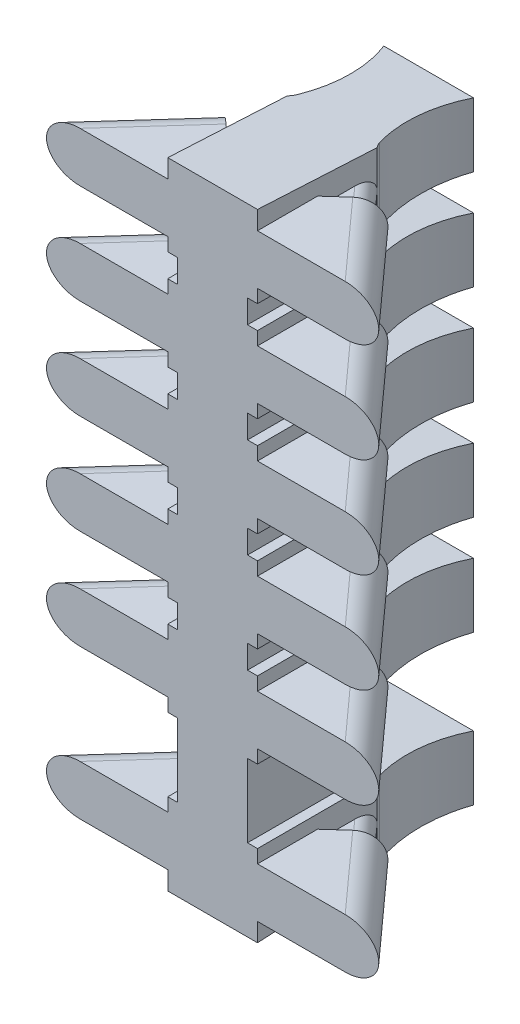
SolidWorks part; units mm, degrees
ref_plane "Front Plane" through (0, 0, 0) normal (0, 0, 1) x (1, 0, 0)
ref_plane "Top Plane" through (0, 0, 0) normal (0, 1, 0) x (1, 0, 0)
ref_plane "Right Plane" through (0, 0, 0) normal (1, 0, 0) x (0, 0, -1)
sketch "Sketch1" plane through (0, 0, 0) normal (0, 0, 1) x (1, 0, 0)
  line L0 (-7.5, 0) -> (0, 0) construction
  line L1 (-7.5, 15) -> (7.5, 15)
  line L2 (-7.5, 15) -> (-7.5, -15)
  line L3 (-7.5, -15) -> (7.5, -15)
  line L4 (7.5, 15) -> (7.5, -15)
  line L5 (0, 0) -> (0, 15) construction
  dimension "D1" = 15
  dimension "D2" = 30
sketch "Sketch2" plane through (0, 0, 0) normal (1, 0, 0) x (0, 0, -1)
  line L1 (0, 15) -> (7, 15)
  line L2 (0, 15) -> (0, -15)
  line L3 (0, -15) -> (7, -15)
  line L4 (7, 15) -> (7, -15)
  dimension "D1" = 7
extrude "Boss-Extrude1" add sketch "Sketch1" against normal up to vertex (7 mm away) up to point (0, 15, -7)
ref_plane "Plane1" through (1.35, 0, 0) normal (1, 0, 0) x (0, 0, -1)
sketch "Sketch7" plane through (1.35, 0, 0) normal (1, 0, 0) x (0, 0, -1)
  line L0 (3, 4.1005) -> (0, 4.1005) construction
  line L1 (0, 4.1005) -> (0, 6.3995) construction
  line L2 (3, 6.3995) -> (0, 6.3995) construction
  line L3 (3, 6.3995) -> (6.5, 6.2161) construction
  line L4 (6.5, 6.2161) -> (6.5, 4.2839) construction
  line L5 (6.5, 4.2839) -> (3, 4.1005) construction
  line L6 (3, 1.1005) -> (0, 1.1005) construction
  line L7 (0, 1.1005) -> (0, 3.3995) construction
  line L8 (3, 3.3995) -> (0, 3.3995) construction
  line L9 (6.5, 3.2161) -> (3, 3.3995) construction
  line L10 (6.5, 1.2839) -> (6.5, 3.2161) construction
  line L11 (3, 1.1005) -> (6.5, 1.2839) construction
  line L12 (3, -1.8995) -> (0, -1.8995) construction
  line L13 (0, -1.8995) -> (0, 0.3995) construction
  line L14 (3, 0.3995) -> (0, 0.3995) construction
  line L15 (3, 0.3995) -> (6.5, 0.2161) construction
  line L16 (6.5, 0.2161) -> (6.5, -1.7161) construction
  line L17 (6.5, -1.7161) -> (3, -1.8995) construction
  line L19 (3, -4.8995) -> (0, -4.8995) construction
  line L20 (0, -4.8995) -> (0, -2.6005) construction
  line L21 (3, -2.6005) -> (0, -2.6005) construction
  line L22 (6.5, -2.7839) -> (3, -2.6005) construction
  line L23 (6.5, -4.7161) -> (6.5, -2.7839) construction
  line L24 (3, -4.8995) -> (6.5, -4.7161) construction
  line L25 (3, -7.1005) -> (0, -7.1005) construction
  line L26 (0, -9.5567) -> (0, -7.1005) construction
  line L27 (6.5, -9.2161) -> (0, -9.5567) construction
  line L28 (6.5, -7.2839) -> (6.5, -9.2161) construction
  line L29 (3, -7.1005) -> (6.5, -7.2839) construction
  line L30 (3, 7.1005) -> (0, 7.1005) construction
  line L31 (0, 7.1005) -> (0, 9.5567) construction
  line L32 (6.5, 9.2161) -> (0, 9.5567) construction
  line L33 (6.5, 7.2839) -> (6.5, 9.2161) construction
  line L34 (3, 7.1005) -> (6.5, 7.2839) construction
  line L35 (3, 4.1005) -> (0, 4.1005)
  line L36 (0, 4.1005) -> (0, 6.3995)
  line L37 (3, 6.3995) -> (0, 6.3995)
  line L38 (3, 6.3995) -> (6.5, 6.2161)
  line L39 (6.5, 6.2161) -> (6.5, 4.2839)
  line L40 (6.5, 4.2839) -> (3, 4.1005)
  line L41 (3, 1.1005) -> (0, 1.1005)
  line L42 (0, 1.1005) -> (0, 3.3995)
  line L43 (3, 3.3995) -> (0, 3.3995)
  line L44 (6.5, 3.2161) -> (3, 3.3995)
  line L45 (6.5, 1.2839) -> (6.5, 3.2161)
  line L46 (3, 1.1005) -> (6.5, 1.2839)
  line L47 (3, -1.8995) -> (0, -1.8995)
  line L48 (0, -1.8995) -> (0, 0.3995)
  line L49 (3, 0.3995) -> (0, 0.3995)
  line L50 (3, 0.3995) -> (6.5, 0.2161)
  line L51 (6.5, 0.2161) -> (6.5, -1.7161)
  line L52 (6.5, -1.7161) -> (3, -1.8995)
  line L54 (3, -4.8995) -> (0, -4.8995)
  line L55 (0, -4.8995) -> (0, -2.6005)
  line L56 (3, -2.6005) -> (0, -2.6005)
  line L57 (6.5, -2.7839) -> (3, -2.6005)
  line L58 (6.5, -4.7161) -> (6.5, -2.7839)
  line L59 (3, -4.8995) -> (6.5, -4.7161)
  line L60 (3, -7.1005) -> (0, -7.1005)
  line L61 (0, -9.5567) -> (0, -7.1005)
  line L62 (6.5, -9.2161) -> (0, -9.5567)
  line L63 (6.5, -7.2839) -> (6.5, -9.2161)
  line L64 (3, -7.1005) -> (6.5, -7.2839)
  line L65 (3, 7.1005) -> (0, 7.1005)
  line L66 (0, 7.1005) -> (0, 9.5567)
  line L67 (6.5, 9.2161) -> (0, 9.5567)
  line L68 (6.5, 7.2839) -> (6.5, 9.2161)
  line L69 (3, 7.1005) -> (6.5, 7.2839)
sketch "Sketch8" plane through (1.35, 0, 0) normal (1, 0, 0) x (0, 0, -1)
  line L0 (6.5, -4.7161) -> (6.5, -2.7839) construction
  line L1 (6.5, -2.7839) -> (3, -2.6005) construction
  line L2 (3, -2.6005) -> (3, -1.8995) construction
  line L3 (6.5, -1.7161) -> (3, -1.8995) construction
  line L4 (6.5, 0.2161) -> (6.5, -1.7161) construction
  line L5 (3, 0.3995) -> (6.5, 0.2161) construction
  line L6 (3, 0.3995) -> (3, 1.1005) construction
  line L7 (3, 1.1005) -> (6.5, 1.2839) construction
  line L8 (6.5, 1.2839) -> (6.5, 3.2161) construction
  line L9 (6.5, 3.2161) -> (3, 3.3995) construction
  line L10 (3, 3.3995) -> (3, 4.1005) construction
  line L11 (6.5, 4.2839) -> (3, 4.1005) construction
  line L12 (6.5, 6.2161) -> (6.5, 4.2839) construction
  line L13 (3, 6.3995) -> (6.5, 6.2161) construction
  line L14 (3, 6.3995) -> (3, 7.1005) construction
  line L15 (3, 7.1005) -> (6.5, 7.2839) construction
  line L16 (6.5, 7.2839) -> (6.5, 9.2161) construction
  line L17 (6.5, 9.2161) -> (0, 9.5567) construction
  line L18 (0, 9.5567) -> (0, -9.5567) construction
  line L19 (6.5, -9.2161) -> (0, -9.5567) construction
  line L20 (6.5, -7.2839) -> (6.5, -9.2161) construction
  line L21 (3, -7.1005) -> (6.5, -7.2839) construction
  line L22 (3, -7.1005) -> (3, -4.8995) construction
  line L23 (3, -4.8995) -> (6.5, -4.7161) construction
  line L24 (6.5, -4.7161) -> (6.5, -2.7839)
  line L25 (6.5, -2.7839) -> (3, -2.6005)
  line L26 (3, -2.6005) -> (3, -1.8995)
  line L27 (6.5, -1.7161) -> (3, -1.8995)
  line L28 (6.5, 0.2161) -> (6.5, -1.7161)
  line L29 (3, 0.3995) -> (6.5, 0.2161)
  line L30 (3, 0.3995) -> (3, 1.1005)
  line L31 (3, 1.1005) -> (6.5, 1.2839)
  line L32 (6.5, 1.2839) -> (6.5, 3.2161)
  line L33 (6.5, 3.2161) -> (3, 3.3995)
  line L34 (3, 3.3995) -> (3, 4.1005)
  line L35 (6.5, 4.2839) -> (3, 4.1005)
  line L36 (6.5, 6.2161) -> (6.5, 4.2839)
  line L37 (3, 6.3995) -> (6.5, 6.2161)
  line L38 (3, 6.3995) -> (3, 7.1005)
  line L39 (3, 7.1005) -> (6.5, 7.2839)
  line L40 (6.5, 7.2839) -> (6.5, 9.2161)
  line L41 (6.5, 9.2161) -> (0, 9.5567)
  line L42 (0, 9.5567) -> (0, -9.5567)
  line L43 (6.5, -9.2161) -> (0, -9.5567)
  line L44 (6.5, -7.2839) -> (6.5, -9.2161)
  line L45 (3, -7.1005) -> (6.5, -7.2839)
  line L46 (3, -7.1005) -> (3, -4.8995)
  line L47 (3, -4.8995) -> (6.5, -4.7161)
sketch "Sketch9" plane through (0, 0, 0) normal (0, 0, 1) x (1, 0, 0)
  line L0 (-1.35, 9.5567) -> (-1.35, -9.5567) construction
  line L1 (1.35, -9.5567) -> (-1.35, -9.5567) construction
  line L2 (1.35, 9.5567) -> (1.35, -9.5567) construction
  line L3 (1.35, 9.5567) -> (-1.35, 9.5567) construction
  line L4 (-1.35, 9.5567) -> (-1.35, -9.5567) construction
  line L5 (1.35, -9.5567) -> (-1.35, -9.5567) construction
  line L6 (1.35, 9.5567) -> (1.35, -9.5567) construction
  line L7 (1.35, 9.5567) -> (-1.35, 9.5567) construction
  line L8 (0, -9.5567) -> (0, 9.5567) construction
  line L9 (-1.35, 0) -> (1.35, 0) construction
  line L10 (0.75, -9.1562) -> (-0.75, -9.1562) construction
  line L11 (-0.75, 9.1562) -> (-0.75, -9.1562) construction
  line L12 (0.75, 9.1562) -> (-0.75, 9.1562) construction
  line L13 (0.75, -9.1562) -> (-0.75, -9.1562)
  line L14 (-0.75, 9.1562) -> (-0.75, -9.1562)
  line L15 (0.75, 9.1562) -> (-0.75, 9.1562)
  line L16 (0.75, -9.1562) -> (0.75, 9.1562)
  line L17 (1.05, -9.5567) -> (1.05, 9.5567) construction
  line L18 (-1.05, -9.5567) -> (-1.05, 9.5567) construction
  line L19 (1.05, -9.5567) -> (1.05, 9.5567) construction
  line L20 (-1.05, -9.5567) -> (-1.05, 9.5567) construction
ref_plane "Plane2" through (0, -9.5567, 0) normal (0, 1, 0) x (1, 0, 0)
sketch "Sketch10" plane through (0, -9.5567, 0) normal (0, 1, 0) x (1, 0, 0)
  line L0 (1.35, 3.5995) -> (1.35, 6.5)
  line L1 (-1.35, 3.5995) -> (-1.35, 6.5)
  arc A0 (-1.2465, 3.7776) -> (-1.35, 6.5) centre (-4.95, 5) ccw construction
  arc A1 (-1.35, 3.5995) -> (-1.2465, 3.7776) centre (-1.7213, 3.9344) ccw construction
  arc A2 (1.2465, 3.7776) -> (1.35, 3.5995) centre (1.7213, 3.9344) ccw construction
  arc A3 (1.35, 6.5) -> (1.2465, 3.7776) centre (4.95, 5) ccw construction
  arc A4 (-1.2465, 3.7776) -> (-1.35, 6.5) centre (-4.95, 5) ccw
  arc A5 (-1.35, 3.5995) -> (-1.2465, 3.7776) centre (-1.7213, 3.9344) ccw
  arc A6 (1.2465, 3.7776) -> (1.35, 3.5995) centre (1.7213, 3.9344) ccw
  arc A7 (1.35, 6.5) -> (1.2465, 3.7776) centre (4.95, 5) ccw
ref_plane "Plane3" through (2.213, 9.1562, -4.3777) normal (0.6697, 0, 0.7426) x (0, -1, 0)
sketch "Sketch11" plane through (2.213, 9.1562, -4.3777) normal (0.6697, 0, 0.7426) x (0, -1, 0)
  line L0 (0.4562, -2.362) -> (0.4562, -1.612) construction
  line L1 (1.3562, -1.612) -> (1.3562, -2.362) construction
  line L2 (1.3562, -2.362) -> (0.4562, -2.362) construction
  line L3 (3.4562, -1.612) -> (3.4562, -2.362) construction
  line L4 (3.4562, -2.362) -> (4.3562, -2.362) construction
  line L5 (4.3562, -2.362) -> (4.3562, -1.612) construction
  line L6 (7.3562, -1.612) -> (7.3562, -2.362) construction
  line L7 (7.3562, -2.362) -> (6.4562, -2.362) construction
  line L8 (6.4562, -2.362) -> (6.4562, -1.612) construction
  line L9 (9.4562, -1.612) -> (9.4562, -2.362) construction
  line L10 (9.4562, -2.362) -> (10.3562, -2.362) construction
  line L11 (10.3562, -2.362) -> (10.3562, -1.612) construction
  line L12 (13.3562, -1.612) -> (13.3562, -2.362) construction
  line L13 (13.3562, -2.362) -> (12.4562, -2.362) construction
  line L14 (12.4562, -2.362) -> (12.4562, -1.612) construction
  line L15 (16.9562, -1.612) -> (16.9562, -2.362) construction
  line L16 (16.9562, -2.362) -> (17.8562, -2.362) construction
  line L17 (17.8562, -2.362) -> (17.8562, -1.612) construction
  line L18 (0.4562, -2.362) -> (0.4562, -1.612)
  line L19 (1.3562, -1.612) -> (1.3562, -2.362)
  line L20 (1.3562, -2.362) -> (0.4562, -2.362)
  line L21 (3.4562, -1.612) -> (3.4562, -2.362)
  line L22 (3.4562, -2.362) -> (4.3562, -2.362)
  line L23 (4.3562, -2.362) -> (4.3562, -1.612)
  line L24 (7.3562, -1.612) -> (7.3562, -2.362)
  line L25 (7.3562, -2.362) -> (6.4562, -2.362)
  line L26 (6.4562, -2.362) -> (6.4562, -1.612)
  line L27 (9.4562, -1.612) -> (9.4562, -2.362)
  line L28 (9.4562, -2.362) -> (10.3562, -2.362)
  line L29 (10.3562, -2.362) -> (10.3562, -1.612)
  line L30 (13.3562, -1.612) -> (13.3562, -2.362)
  line L31 (13.3562, -2.362) -> (12.4562, -2.362)
  line L32 (12.4562, -2.362) -> (12.4562, -1.612)
  line L33 (16.9562, -1.612) -> (16.9562, -2.362)
  line L34 (16.9562, -2.362) -> (17.8562, -2.362)
  line L35 (17.8562, -2.362) -> (17.8562, -1.612)
  arc A0 (1.3562, -1.612) -> (0.4562, -1.612) centre (0.9062, -1.612) ccw construction
  arc A1 (4.3562, -1.612) -> (3.4562, -1.612) centre (3.9062, -1.612) ccw construction
  arc A2 (7.3562, -1.612) -> (6.4562, -1.612) centre (6.9062, -1.612) ccw construction
  arc A3 (10.3562, -1.612) -> (9.4562, -1.612) centre (9.9062, -1.612) ccw construction
  arc A4 (13.3562, -1.612) -> (12.4562, -1.612) centre (12.9062, -1.612) ccw construction
  arc A5 (17.8562, -1.612) -> (16.9562, -1.612) centre (17.4062, -1.612) ccw construction
  arc A6 (1.3562, -1.612) -> (0.4562, -1.612) centre (0.9062, -1.612) ccw
  arc A7 (4.3562, -1.612) -> (3.4562, -1.612) centre (3.9062, -1.612) ccw
  arc A8 (7.3562, -1.612) -> (6.4562, -1.612) centre (6.9062, -1.612) ccw
  arc A9 (10.3562, -1.612) -> (9.4562, -1.612) centre (9.9062, -1.612) ccw
  arc A10 (13.3562, -1.612) -> (12.4562, -1.612) centre (12.9062, -1.612) ccw
  arc A11 (17.8562, -1.612) -> (16.9562, -1.612) centre (17.4062, -1.612) ccw
ref_plane "Plane4" through (3.1041, 9.1562, -3.3895) normal (0.6697, 0, 0.7426) x (0, -1, 0)
sketch "Sketch12" plane through (3.1041, 9.1562, -3.3895) normal (0.6697, 0, 0.7426) x (0, -1, 0)
  line L0 (0.1562, -1.612) -> (0.1562, -5.0612) construction
  line L1 (0.1562, -5.0612) -> (1.6562, -5.0612) construction
  line L2 (1.6562, -1.612) -> (1.6562, -5.0612) construction
  line L3 (3.1562, -1.612) -> (3.1562, -5.0612) construction
  line L4 (4.6562, -5.0612) -> (3.1562, -5.0612) construction
  line L5 (4.6562, -1.612) -> (4.6562, -5.0612) construction
  line L6 (6.1562, -1.612) -> (6.1562, -5.0612) construction
  line L7 (6.1562, -5.0612) -> (7.6562, -5.0612) construction
  line L8 (7.6562, -1.612) -> (7.6562, -5.0612) construction
  line L9 (9.1562, -1.612) -> (9.1562, -5.0612) construction
  line L10 (10.6562, -5.0612) -> (9.1562, -5.0612) construction
  line L11 (10.6562, -1.612) -> (10.6562, -5.0612) construction
  line L12 (12.1562, -1.612) -> (12.1562, -5.0612) construction
  line L13 (12.1562, -5.0612) -> (13.6562, -5.0612) construction
  line L14 (13.6562, -1.612) -> (13.6562, -5.0612) construction
  line L15 (16.6562, -1.612) -> (16.6562, -5.0612) construction
  line L16 (18.1562, -5.0612) -> (16.6562, -5.0612) construction
  line L17 (18.1562, -1.612) -> (18.1562, -5.0612) construction
  line L18 (0.1562, -1.612) -> (0.1562, -5.0612)
  line L19 (0.1562, -5.0612) -> (1.6562, -5.0612)
  line L20 (1.6562, -1.612) -> (1.6562, -5.0612)
  line L21 (3.1562, -1.612) -> (3.1562, -5.0612)
  line L22 (4.6562, -5.0612) -> (3.1562, -5.0612)
  line L23 (4.6562, -1.612) -> (4.6562, -5.0612)
  line L24 (6.1562, -1.612) -> (6.1562, -5.0612)
  line L25 (6.1562, -5.0612) -> (7.6562, -5.0612)
  line L26 (7.6562, -1.612) -> (7.6562, -5.0612)
  line L27 (9.1562, -1.612) -> (9.1562, -5.0612)
  line L28 (10.6562, -5.0612) -> (9.1562, -5.0612)
  line L29 (10.6562, -1.612) -> (10.6562, -5.0612)
  line L30 (12.1562, -1.612) -> (12.1562, -5.0612)
  line L31 (12.1562, -5.0612) -> (13.6562, -5.0612)
  line L32 (13.6562, -1.612) -> (13.6562, -5.0612)
  line L33 (16.6562, -1.612) -> (16.6562, -5.0612)
  line L34 (18.1562, -5.0612) -> (16.6562, -5.0612)
  line L35 (18.1562, -1.612) -> (18.1562, -5.0612)
  arc A0 (1.6562, -1.612) -> (0.1562, -1.612) centre (0.9062, -1.612) ccw construction
  arc A1 (4.6562, -1.612) -> (3.1562, -1.612) centre (3.9062, -1.612) ccw construction
  arc A2 (7.6562, -1.612) -> (6.1562, -1.612) centre (6.9062, -1.612) ccw construction
  arc A3 (10.6562, -1.612) -> (9.1562, -1.612) centre (9.9062, -1.612) ccw construction
  arc A4 (13.6562, -1.612) -> (12.1562, -1.612) centre (12.9062, -1.612) ccw construction
  arc A5 (18.1562, -1.612) -> (16.6562, -1.612) centre (17.4062, -1.612) ccw construction
  arc A6 (1.6562, -1.612) -> (0.1562, -1.612) centre (0.9062, -1.612) ccw
  arc A7 (4.6562, -1.612) -> (3.1562, -1.612) centre (3.9062, -1.612) ccw
  arc A8 (7.6562, -1.612) -> (6.1562, -1.612) centre (6.9062, -1.612) ccw
  arc A9 (10.6562, -1.612) -> (9.1562, -1.612) centre (9.9062, -1.612) ccw
  arc A10 (13.6562, -1.612) -> (12.1562, -1.612) centre (12.9062, -1.612) ccw
  arc A11 (18.1562, -1.612) -> (16.6562, -1.612) centre (17.4062, -1.612) ccw
extrude "Cut-Extrude1" cut sketch "Sketch8" against normal up to vertex (2.4 mm away) from vertex at -0.3 starting at point (1.05, -9.5567, 0)
extrude "Cut-Extrude4" cut sketch "Sketch7" against normal up to vertex (2.7 mm away) up to point (-1.35, -9.5567, 0)
extrude "Boss-Extrude2" add sketch "Sketch10" along normal up to vertex (24.5567 mm away)
extrude "Cut-Extrude2" cut sketch "Sketch12" along normal through all
extrude "Cut-Extrude3" cut sketch "Sketch11" along normal through all
mirror "Mirror1" about plane through (0, 0, 0) normal (1, 0, 0) of "Cut-Extrude2", "Cut-Extrude3"
sketch "Sketch13" plane through (0, 0, 0) normal (0, 0, 1) x (1, 0, 0)
  line L0 (0, 0) -> (-5, 0) construction
  line L1 (-5, -10) -> (5, -10)
  line L2 (-5, -10) -> (-5, 10)
  line L3 (-5, 10) -> (5, 10)
  line L4 (5, -10) -> (5, 10)
  line L5 (0, 0) -> (5, 0) construction
  line L6 (0, 0) -> (0, 10) construction
  line L7 (0, 0) -> (0, -10) construction
  dimension "D1" = 20
  dimension "D2" = 10
extrude "Boss-Extrude3" add sketch "Sketch13" against normal blind 7 separate body
combine bodies "Combine1" operation type subtract main body 114 bodies to subtract 112
